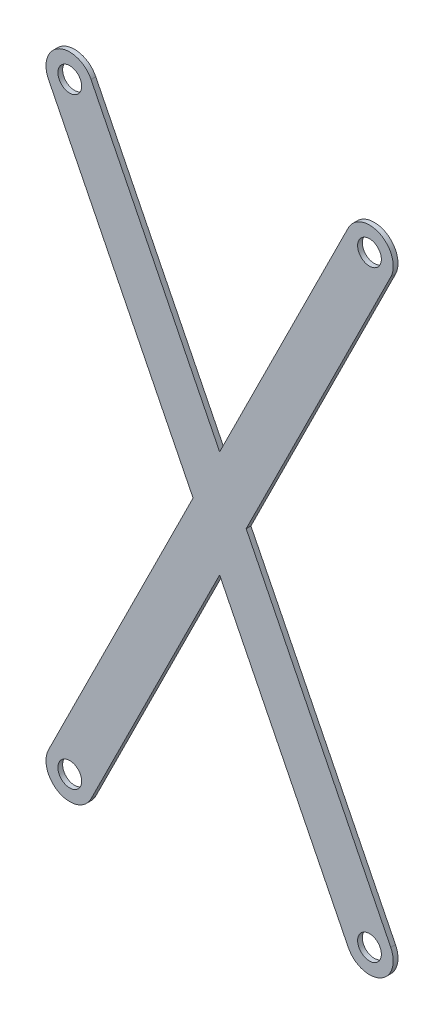
SolidWorks part; units mm, degrees
ref_plane "前视基准面" through (0, 0, 0) normal (0, 0, 1) x (1, 0, 0)
ref_plane "上视基准面" through (0, 0, 0) normal (0, 1, 0) x (1, 0, 0)
ref_plane "右视基准面" through (0, 0, 0) normal (1, 0, 0) x (0, 0, -1)
other "Configuration Table"
sketch "草图2" plane through (0, 0, 0) normal (0, 0, 1) x (1, 0, 0)
  line L0 (0, 0) -> (189.2634, 380) construction
  line L1 (-13.4268, 6.6874) -> (77.8742, 190)
  line L2 (13.4268, -6.6874) -> (94.6317, 156.3545)
  line L3 (0, 380) -> (189.2634, 0) construction
  line L4 (13.4268, 386.6874) -> (94.6317, 223.6455)
  line L5 (-13.4268, 373.3126) -> (77.8742, 190)
  line L6 (94.6317, 156.3545) -> (175.8366, -6.6874)
  line L7 (111.3892, 190) -> (202.6902, 6.6874)
  line L8 (94.6317, 223.6455) -> (175.8366, 386.6874)
  line L9 (111.3892, 190) -> (202.6902, 373.3126)
  arc A0 (-13.4268, 6.6874) -> (13.4268, -6.6874) centre (0, 0) ccw
  arc A1 (202.6902, 373.3126) -> (175.8366, 386.6874) centre (189.2634, 380) ccw
  circle A2 centre (0, 0) radius 7.5
  circle A3 centre (189.2634, 380) radius 7.5
  arc A4 (13.4268, 386.6874) -> (-13.4268, 373.3126) centre (0, 380) ccw
  arc A5 (175.8366, -6.6874) -> (202.6902, 6.6874) centre (189.2634, 0) ccw
  circle A6 centre (189.2634, 0) radius 7.5
  circle A7 centre (0, 380) radius 7.5
  point P4 (94.6317, 190)
  point P18 (94.6317, 190)
  dimension "D2" = 15
  dimension "D3" = 15
  dimension "D5" = 15
  dimension "D6" = 15
  dimension "D1" = 30
  dimension "D4" = 30
extrude "凸台-拉伸1" add sketch "草图2" along normal blind 3
